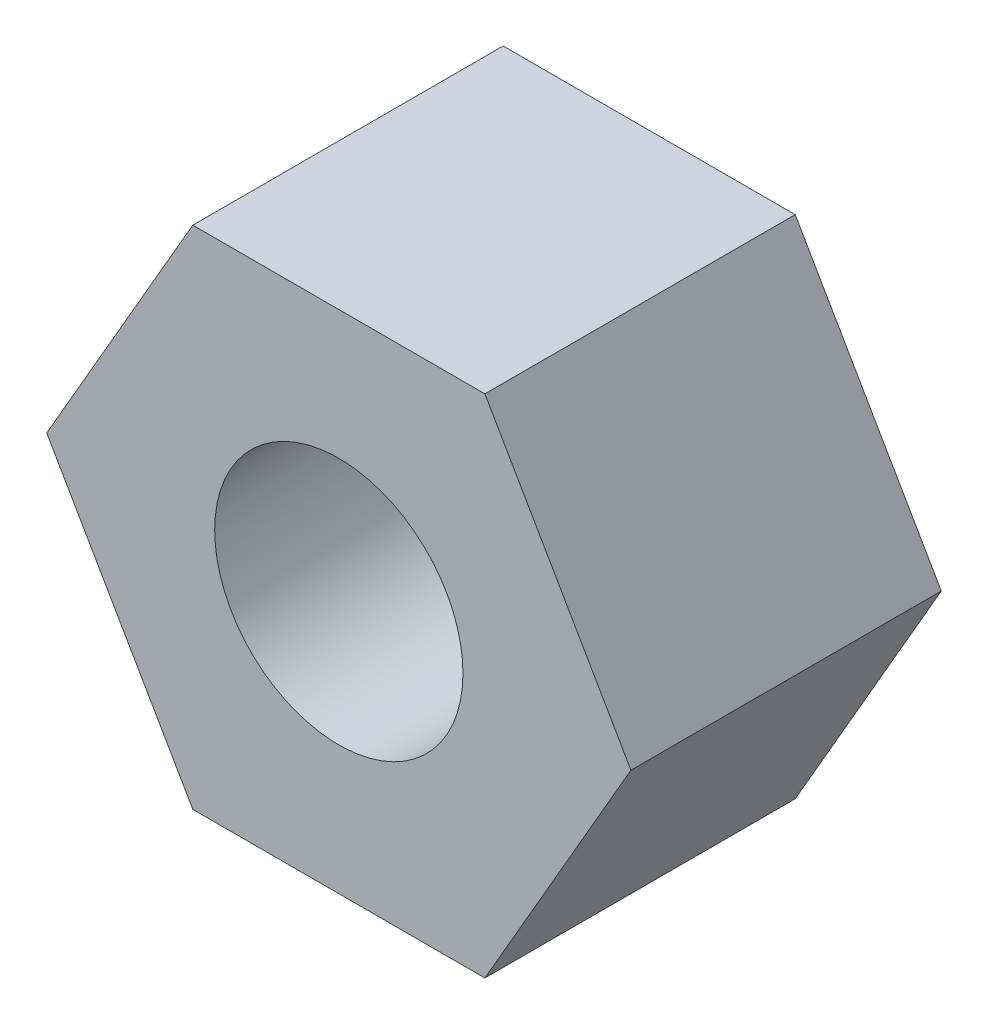
SolidWorks part; units mm, degrees
ref_plane "Front Plane" through (0, 0, 0) normal (0, 0, 1) x (1, 0, 0)
ref_plane "Top Plane" through (0, 0, 0) normal (0, 1, 0) x (1, 0, 0)
ref_plane "Right Plane" through (0, 0, 0) normal (1, 0, 0) x (0, 0, -1)
sketch "Sketch1" plane through (0, 0, 0) normal (0, 0, 1) x (1, 0, 0)
  line L1 (2, -3.4641) -> (4, 0)
  line L2 (4, 0) -> (2, 3.4641)
  line L3 (2, 3.4641) -> (-2, 3.4641)
  line L4 (-2, 3.4641) -> (-4, 0)
  line L5 (-4, 0) -> (-2, -3.4641)
  line L6 (-2, -3.4641) -> (2, -3.4641)
  circle A0 centre (0, 0) radius 3.4641 construction
  point P1 (0, 3.4641)
  dimension "D1" = 4
extrude "Boss-Extrude1" add sketch "Sketch1" along normal mid plane 4.25
hole_wizard "CSK for M3 Countersunk Flat Head Screw1" positions "Sketch4" profile "Sketch5" countersink size "M3" standard "DIN"
sketch "Sketch4" plane through (0, 0, -2.125) normal (0, 0, -1) x (-1, 0, 0)
  point P0 (0, 0)
sketch "Sketch5" plane through (0, 0, -2.125) normal (1, 0, 0) x (0, 1, 0)
  line L0 (0, 0) -> (0, 6.0215)
  line L1 (0, 6.0215) -> (1.7, 5)
  line L2 (1.7, 5) -> (1.7, 1.45)
  line L3 (1.7, 1.45) -> (3.15, 0)
  line L5 (3.15, 0) -> (0, 0)
  line L6 (-1.7, 1.45) -> (-3.15, 0) construction
  line L10 (0, 6.0215) -> (-1.7, 5) construction
  line L11 (0, -6.35) -> (0, 107.95) construction
  dimension "Hole Dia." = 3.4
  dimension "Hole Depth" = 5
  dimension "Near C'Sink Dia." = 6.3
  dimension "Near C'Sink Angle" = 90
  dimension "Drill Angle" = 118
